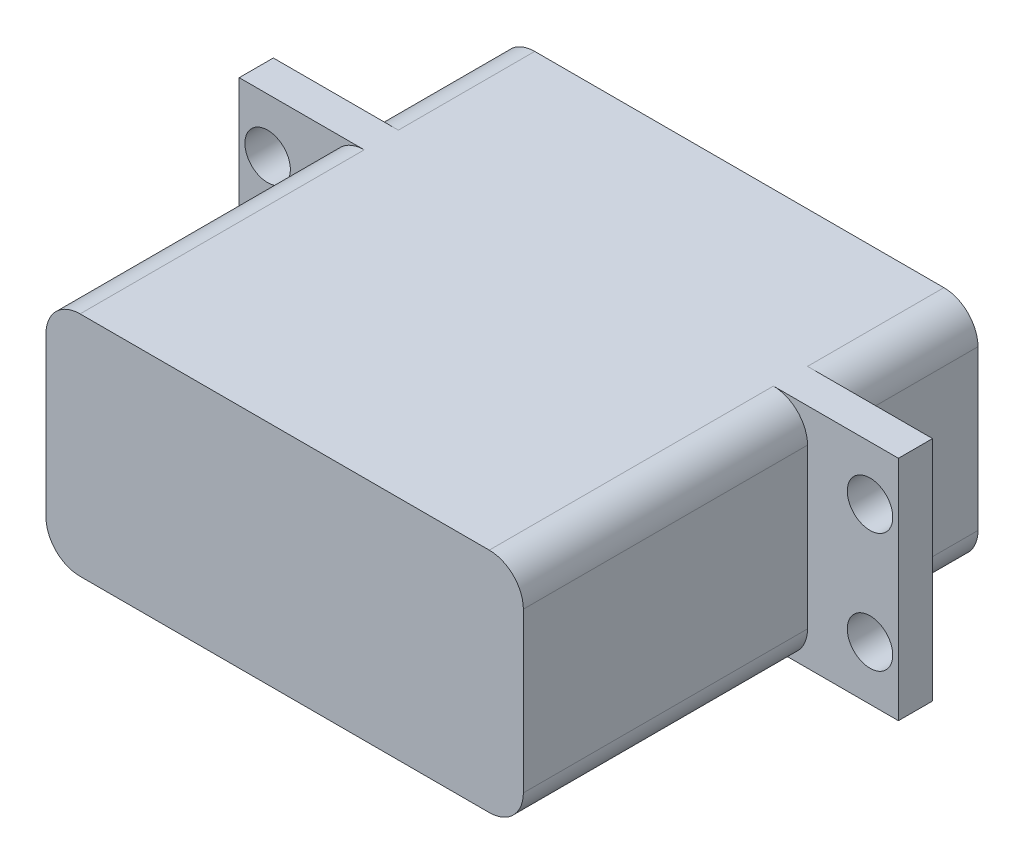
SolidWorks part; units mm, degrees
ref_plane "Front" through (0, 0, 0) normal (0, 0, 1) x (1, 0, 0)
ref_plane "Top" through (0, 0, 0) normal (0, 1, 0) x (1, 0, 0)
ref_plane "Right" through (0, 0, 0) normal (1, 0, 0) x (0, 0, -1)
sketch "草图1" plane through (0, 0, 0) normal (0, 0, 1) x (1, 0, 0)
  line L1 (3, 0) -> (39, 0)
  line L2 (0, -3) -> (0, -17)
  line L3 (3, -20) -> (39, -20)
  line L4 (42, -3) -> (42, -17)
  arc A0 (39, -20) -> (42, -17) centre (39, -17) ccw
  arc A1 (39, 0) -> (42, -3) centre (39, -3) cw
  arc A2 (3, -20) -> (0, -17) centre (3, -17) cw
  arc A3 (3, 0) -> (0, -3) centre (3, -3) ccw
  point P7 (42, -20)
  point P10 (42, 0)
  point P15 (0, 0)
  dimension "D3" = 3
  dimension "D1" = 42
  dimension "D2" = 20
extrude "凸台-拉伸1" add sketch "草图1" along normal blind 40
ref_plane "基准面1" through (0, 0, 12) normal (0, 0, 1) x (1, 0, 0)
sketch "草图3" plane through (0, 0, 12) normal (0, 0, 1) x (1, 0, 0)
  line L0 (0, -17) -> (-8, -17) construction
  line L1 (0, -3) -> (-8, -3) construction
  line L2 (3, 0) -> (-8, 0)
  line L3 (-8, 0) -> (-8, -20)
  line L4 (-8, -20) -> (3, -20)
  line L5 (0, -3) -> (0, -17)
  line L6 (21, 0) -> (21, -20) construction
  line L7 (39, 0) -> (3, 0) construction
  line L8 (3, -20) -> (39, -20) construction
  line L9 (42, -3) -> (42, -17)
  line L10 (39, 0) -> (50, 0)
  line L11 (50, 0) -> (50, -20)
  line L12 (50, -20) -> (39, -20)
  arc A0 (3, 0) -> (0, -3) centre (3, -3) ccw
  arc A1 (0, -17) -> (3, -20) centre (3, -17) ccw
  arc A2 (39, 0) -> (42, -3) centre (39, -3) cw
  arc A3 (42, -17) -> (39, -20) centre (39, -17) cw
extrude "凸台-拉伸2" add sketch "草图3" along normal blind 3
sketch "草图4" plane through (0, 0, 12) normal (0, 0, -1) x (-1, 0, 0)
  line L0 (0, -10) -> (8, -10) construction
  line L1 (0, -17) -> (0, -3) construction
  line L2 (8, 0) -> (8, -20) construction
  line L3 (0, -10) -> (5.5, -10)
  line L4 (5.5, -15.25) -> (5.5, -4.75)
  line L5 (-21, 0) -> (-21, -20) construction
  line L6 (-39, 0) -> (-3, 0) construction
  line L7 (-3, -20) -> (-39, -20) construction
  circle A0 centre (5.5, -4.75) radius 2
  circle A1 centre (5.5, -15.25) radius 2
  circle A2 centre (-47.5, -4.75) radius 2
  circle A3 centre (-47.5, -15.25) radius 2
extrude "切除-拉伸1" cut sketch "草图4" against normal blind 3
sketch "草图5" plane through (0, 0, 0) normal (0, 0, -1) x (-1, 0, 0)
  line L0 (0, -10) -> (-10, -10) construction
  line L1 (0, -3) -> (0, -17) construction
  circle A0 centre (-10, -10) radius 3
extrude "凸台-拉伸3" add sketch "草图5" along normal blind 5.5
